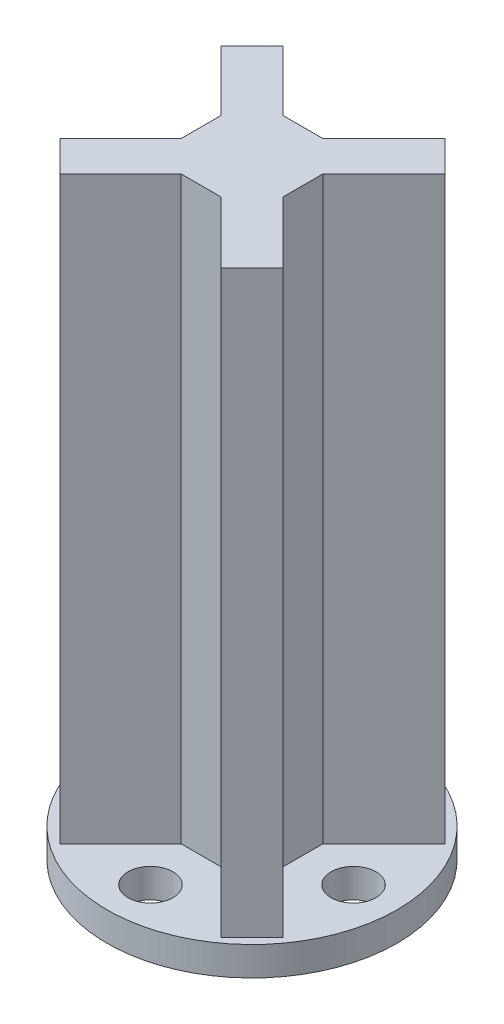
SolidWorks part; units mm, degrees
ref_plane "Płaszczyzna przednia" through (0, 0, 0) normal (0, 0, 1) x (1, 0, 0)
ref_plane "Płaszczyzna górna" through (0, 0, 0) normal (0, 1, 0) x (1, 0, 0)
ref_plane "Płaszczyzna prawa" through (0, 0, 0) normal (1, 0, 0) x (0, 0, -1)
sketch "Sketch1" plane through (0, 0, 0) normal (0, 0, 1) x (1, 0, 0)
  circle A0 centre (0, 0) radius 10
  circle A1 centre (-7, 0) radius 1.55
  circle A2 centre (0, 7) radius 1.55
  circle A3 centre (0, -7) radius 1.55
  circle A4 centre (7, 0) radius 1.55
extrude "Boss-Extrude1" add sketch "Sketch1" along normal blind 2
sketch "Sketch2" plane through (0, 0, 2) normal (0, 0, 1) x (1, 0, 0)
  line L0 (-6.6227, -6.6227) -> (-7.0711, -7.0711) construction
  line L1 (-1.3787, -3.5) -> (1.3787, -3.5)
  line L2 (-3.5, -1.3787) -> (-3.5, 1.3787)
  line L3 (-1.3787, 3.5) -> (1.3787, 3.5)
  line L4 (3.5, -1.3787) -> (3.5, 1.3787)
  line L7 (-1.3787, -3.5) -> (-5.562, -7.6833)
  line L8 (-3.5, -1.3787) -> (-7.6833, -5.562)
  line L9 (-6.581, 6.581) -> (-7.0711, 7.0711) construction
  line L11 (6.6453, 6.6453) -> (7.0711, 7.0711) construction
  line L13 (-1.3787, 3.5) -> (-5.5203, 7.6417)
  line L25 (-3.5, 1.3787) -> (-7.6417, 5.5203)
  line L26 (-5.5203, 7.6417) -> (-7.6417, 5.5203)
  line L28 (1.3787, -3.5) -> (5.6033, -7.7247)
  line L30 (5.6033, -7.7247) -> (7.7247, -5.6033)
  line L42 (-7.6833, -5.562) -> (-5.562, -7.6833)
  line L44 (1.3787, 3.5) -> (5.5847, 7.706)
  line L45 (3.5, 1.3787) -> (7.706, 5.5847)
  line L46 (5.5847, 7.706) -> (7.706, 5.5847)
  line L47 (3.5, -1.3787) -> (7.7247, -5.6033)
  line L48 (6.664, -6.664) -> (7.0711, -7.0711) construction
  circle A2 centre (7, 0) radius 3
  circle A3 centre (0, 7) radius 3
  circle A4 centre (-7, 0) radius 3
  circle A5 centre (0, -7) radius 3
  circle A6 centre (0, 0) radius 10 construction
extrude "Boss-Extrude2" add sketch "Sketch2" along normal blind 40 contours L4 L45 L46 L44 L3 L13 L26 L25 L2 L8 L42 L7 L1 L28 L30 L47
move or copy body "Body-Move/Copy1" bodies to move or copy 102 copy no rotation origin (0, 0, 21) rotation axis (-1, 0, 0) rotation angle 90
